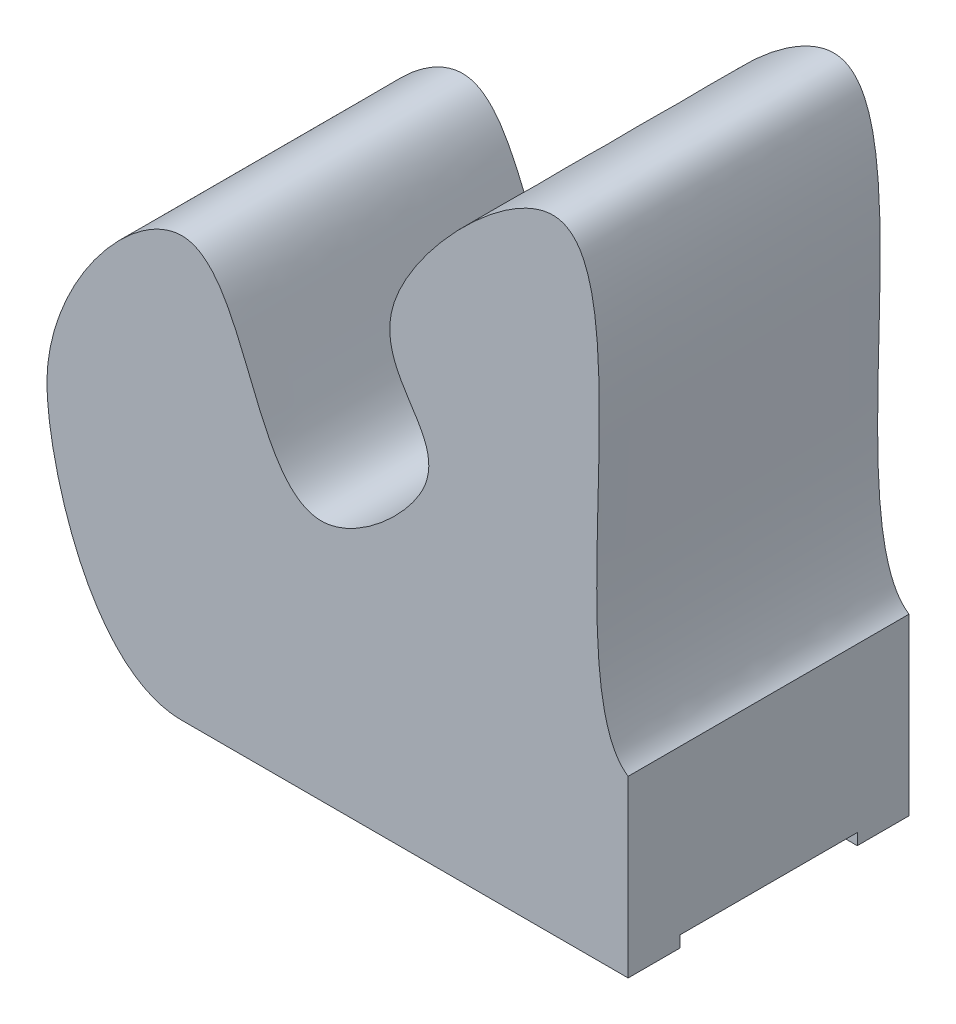
SolidWorks part; units mm, degrees
ref_plane "Front Plane" through (0, 0, 0) normal (0, 0, 1) x (1, 0, 0)
ref_plane "Top Plane" through (0, 0, 0) normal (0, 1, 0) x (1, 0, 0)
ref_plane "Right Plane" through (0, 0, 0) normal (1, 0, 0) x (0, 0, -1)
sketch "Sketch1" plane through (0, 0, 0) normal (0, 0, 1) x (1, 0, 0)
  line L0 (0, 0) -> (19.05, 0)
  line L1 (19.05, 0) -> (19.05, 7.4555)
  spline S0 degree 3 poles (19.05, 7.4555) (15.8656, 9.5325) (21.9219, 34.9861) (5.2643, 17.7197) (13.3165, 15.6309) (3.0702, 6.429) (2.7288, 23.0972) (-5.4875, 13.8702) (-5.9596, 7.4669) (-3.6629, 0) (0, 0) knots 0 0 0 0 0.255088 0.380225 0.524451 0.608262 0.787372 0.906221 0.927484 1 1 1 1
  dimension "D1" = 19.05
extrude "Boss-Extrude1" add sketch "Sketch1" along normal mid plane 11.9888
sketch "Sketch2" plane through (0, 0, 0) normal (1, 0, 0) x (0, 0, -1)
  line L0 (-3.7854, -0.487) -> (3.7854, -0.487)
  line L1 (-3.7854, -0.487) -> (-3.7854, 0.487)
  line L2 (3.7854, -0.487) -> (3.7854, 0.487)
  line L3 (-3.7854, 0.487) -> (3.7854, 0.487)
  line L4 (-3.7854, -0.487) -> (3.7854, 0.487) construction
  line L5 (3.7854, -0.487) -> (-3.7854, 0.487) construction
  point P1 (0, 0)
extrude "Cut-Extrude1" cut sketch "Sketch2" along normal through all
fillet "Fillet1" radius 2.54 2 edges at (0, 0.2435, -3.7854) (0, 0.2435, 3.7854)
